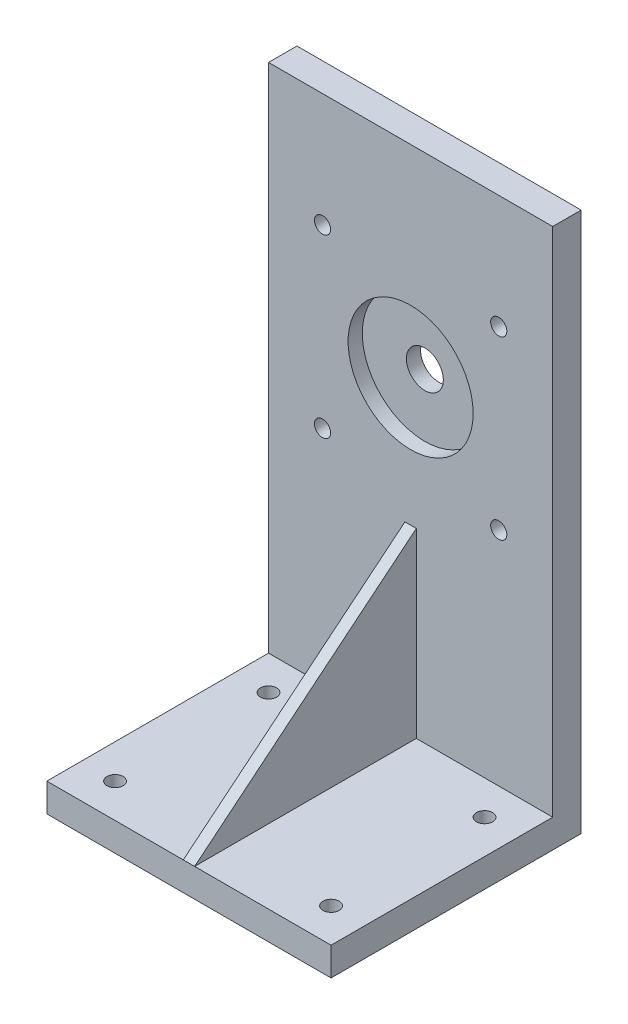
SolidWorks part; units mm, degrees
ref_plane "Front Plane" through (0, 0, 0) normal (0, 0, 1) x (1, 0, 0)
ref_plane "Top Plane" through (0, 0, 0) normal (0, 1, 0) x (1, 0, 0)
ref_plane "Right Plane" through (0, 0, 0) normal (1, 0, 0) x (0, 0, -1)
sketch "Sketch1" plane through (0, 0, 0) normal (0, 1, 0) x (1, 0, 0)
  line L1 (-25, -22) -> (25, -22)
  line L2 (-25, -22) -> (-25, 22)
  line L3 (-25, 22) -> (25, 22)
  line L4 (25, -22) -> (25, 22)
  line L5 (-25, -22) -> (25, 22) construction
  line L6 (-25, 22) -> (25, -22) construction
  point P0 (0, 0)
  dimension "D1" = 50
  dimension "D2" = 44
extrude "Boss-Extrude1" add sketch "Sketch1" along normal blind 5
sketch "Sketch2" plane through (0, 5, 0) normal (0, 1, 0) x (1, 0, 0)
  line L0 (25, -22) -> (25, 22) construction
  line L1 (-25, 22) -> (25, 22)
  line L2 (-25, 22) -> (-25, 17)
  line L3 (-25, 17) -> (25, 17)
  line L4 (25, 22) -> (25, 17)
  dimension "D1" = 5
extrude "Boss-Extrude2" add sketch "Sketch2" along normal blind 90
sketch "Sketch3" plane through (0, 0, -17) normal (0, 0, 1) x (1, 0, 0)
  line L0 (-25, 5) -> (25, 5) construction
  line L2 (-25, 95) -> (-25, 5) construction
  circle A0 centre (-15.5, 44) radius 1.42
  circle A1 centre (15.5, 44) radius 1.42
  circle A2 centre (15.5, 75) radius 1.42
  circle A3 centre (-15.5, 75) radius 1.42
  dimension "D2" = 2.84
  dimension "D1" = 39
  dimension "D3" = 2
  dimension "D5" = 9.5
  dimension "D4" = 2
extrude "Cut-Extrude1" cut sketch "Sketch3" against normal blind 60
sketch "Sketch4" plane through (0, 0, -17) normal (0, 0, 1) x (1, 0, 0)
  circle A0 centre (0, 59.5) radius 11
  circle A1 centre (15.5, 44) radius 1.42 construction
  circle A2 centre (15.5, 75) radius 1.42 construction
  dimension "D1" = 22
  dimension "D2" = 15.5
  dimension "D3" = 15.5
extrude "Cut-Extrude2" cut sketch "Sketch4" against normal blind 2.5
sketch "Sketch5" plane through (0, 0, -19.5) normal (0, 0, 1) x (1, 0, 0)
  circle A0 centre (0, 59.5) radius 3.25
  dimension "D1" = 6.5
extrude "Cut-Extrude3" cut sketch "Sketch5" against normal blind 10
sketch "Sketch6" plane through (0, 5, 0) normal (0, 1, 0) x (1, 0, 0)
  line L0 (-25, 17) -> (-25, -22) construction
  line L1 (25, -22) -> (25, 17) construction
  line L2 (-25, -22) -> (25, -22) construction
  line L3 (-25, 17) -> (25, 17) construction
  circle A0 centre (-19, 11) radius 1.42
  circle A1 centre (-19, -16) radius 1.42
  circle A2 centre (19, -16) radius 1.42
  circle A3 centre (19, 11) radius 1.42
  dimension "D1" = 2.84
  dimension "D10" = 2.84
  dimension "D11" = 2.84
  dimension "D12" = 2.84
  dimension "D2" = 6
  dimension "D3" = 6
  dimension "D4" = 6
  dimension "D5" = 6
  dimension "D6" = 6
  dimension "D7" = 6
  dimension "D8" = 6
  dimension "D9" = 6
extrude "Cut-Extrude4" cut sketch "Sketch6" against normal blind 10
sketch "Sketch8" plane through (0, 5, 0) normal (0, 1, 0) x (1, 0, 0)
  line L0 (-25, 17) -> (25, 17) construction
  line L1 (1, 17) -> (-1, 17)
  line L2 (1, 17) -> (1, -22)
  line L3 (1, -22) -> (-1, -22)
  line L4 (-1, 17) -> (-1, -22)
  line L5 (-25, -22) -> (25, -22) construction
  circle A0 centre (-19, 11) radius 1.42 construction
  circle A1 centre (19, 11) radius 1.42 construction
  dimension "D1" = 20
  dimension "D2" = 20
  dimension "D3" = 0
extrude "Boss-Extrude3" add sketch "Sketch8" along normal blind 32
sketch "Sketch9" plane through (1, 0, 0) normal (1, 0, 0) x (0, 0, -1)
  line L0 (17, 37) -> (-22, 5)
  line L1 (-22, 37) -> (-22, 5) construction
  line L2 (-22, 5) -> (-22, 37)
  line L3 (-22, 37) -> (17, 37)
extrude "Cut-Extrude5" cut sketch "Sketch9" against normal blind 35
